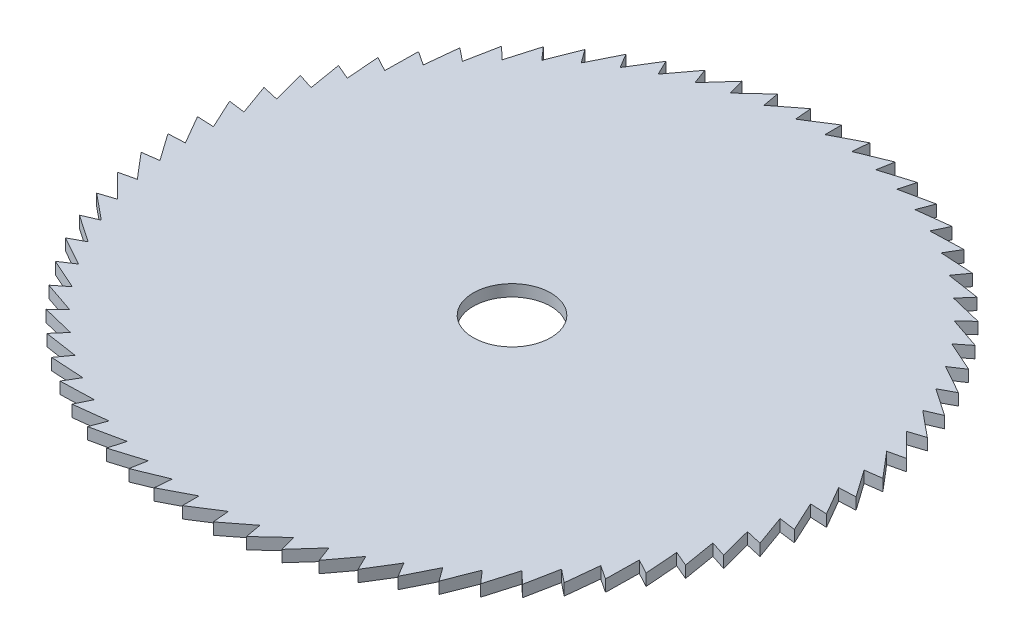
SolidWorks part; units mm, degrees
ref_plane "정면" through (0, 0, 0) normal (0, 0, 1) x (1, 0, 0)
ref_plane "윗면" through (0, 0, 0) normal (0, 1, 0) x (1, 0, 0)
ref_plane "우측면" through (0, 0, 0) normal (1, 0, 0) x (0, 0, -1)
sketch "스케치1" plane through (0, 0, 0) normal (0, 1, 0) x (1, 0, 0)
  circle A0 centre (0, 0) radius 25.5
  circle A1 centre (0, 0) radius 3
  dimension "D1" = 51
  dimension "D2" = 6
extrude "보스-돌출1" add sketch "스케치1" along normal blind 0.9
sketch "스케치3" plane through (0, 0.9, 0) normal (0, 1, 0) x (1, 0, 0)
  line L0 (0, 0) -> (0, 28.1575) construction
  line L1 (0, 25.5) -> (0, 24.2)
  line L2 (0, 25.5) -> (0, 26.1749)
  line L3 (0, 26.1749) -> (3.7978, 26.1749)
  line L4 (3.7978, 26.1749) -> (0, 24.2)
  line L5 (2.3, 25.3961) -> (0, 25.3961) construction
  circle A0 centre (0, 0) radius 25.5 construction
  dimension "D1" = 1.3
  dimension "D2" = 2.3
extrude "컷-돌출2" cut sketch "스케치3" against normal blind 0.9
pattern_circular "원형 패턴1" count 70 over 360 about axis through (0, 0, 0) along (0, 1, 0) of "컷-돌출2"
